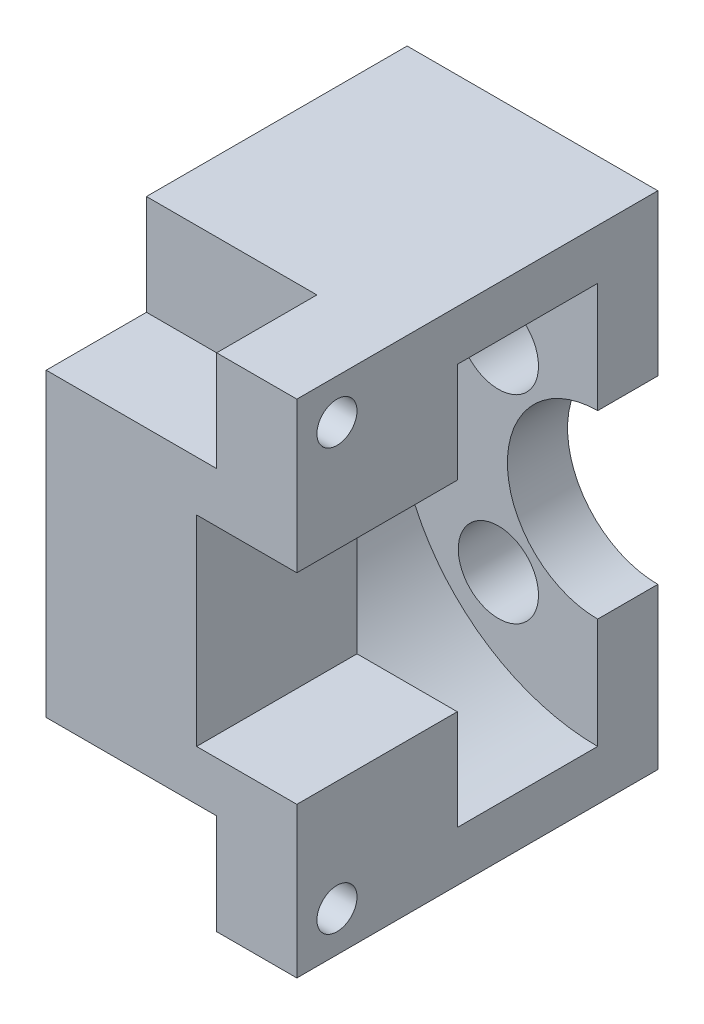
SolidWorks part; units mm, degrees
ref_plane "前视基准面" through (0, 0, 0) normal (0, 0, 1) x (1, 0, 0)
ref_plane "上视基准面" through (0, 0, 0) normal (0, 1, 0) x (1, 0, 0)
ref_plane "右视基准面" through (0, 0, 0) normal (1, 0, 0) x (0, 0, -1)
sketch "草图1" plane through (0, 0, 0) normal (0, 0, 1) x (1, 0, 0)
  line L1 (-12.5, -12.5) -> (12.5, -12.5)
  line L2 (-12.5, -12.5) -> (-12.5, 12.5)
  line L3 (-12.5, 12.5) -> (12.5, 12.5)
  line L4 (12.5, -12.5) -> (12.5, 12.5)
  line L5 (-12.5, -12.5) -> (12.5, 12.5) construction
  line L6 (-12.5, 12.5) -> (12.5, -12.5) construction
  point P0 (0, 0)
  dimension "D1" = 25
  dimension "D2" = 25
extrude "凸台-拉伸1" add sketch "草图1" along normal blind 10
sketch "草图2" plane through (0, 0, 10) normal (0, 0, 1) x (1, 0, 0)
  circle A0 centre (0, 0) radius 10
  dimension "D1" = 20
extrude "切除-拉伸1" cut sketch "草图2" against normal offset from surface (7 mm away) 3 up to face at (0, 0, 0)
sketch "草图3" plane through (0, 0, 3) normal (0, 0, 1) x (1, 0, 0)
  circle A0 centre (0, 0) radius 4.5
  dimension "D1" = 9
extrude "切除-拉伸2" cut sketch "草图3" against normal through all
sketch "草图4" plane through (0, 0, 3) normal (0, 0, 1) x (1, 0, 0)
  line L0 (-12.5, 12.5) -> (0, 0) construction
  circle A0 centre (-4.9497, 4.9497) radius 2
  dimension "D1" = 4
  dimension "D2" = 7
extrude "切除-拉伸4" cut sketch "草图4" against normal through all
pattern_circular "阵列(圆周)1" count 4 over 360 about axis through (0, 0, 0) along (0, 0, 1) of "切除-拉伸4"
sketch "草图5" plane through (0, 0, 10) normal (0, 0, 1) x (1, 0, 0)
  line L0 (-12.5, -12.5) -> (12.5, -12.5) construction
  line L1 (12.5, -12.5) -> (12.5, 12.5) construction
  line L2 (12.5, 12.5) -> (-12.5, 12.5) construction
  line L3 (-12.5, 12.5) -> (-12.5, -12.5) construction
  line L4 (-12.5, -12.5) -> (12.5, -12.5)
  line L5 (12.5, -12.5) -> (12.5, 12.5)
  line L6 (12.5, 12.5) -> (-12.5, 12.5)
  line L7 (-12.5, 12.5) -> (-12.5, -12.5)
extrude "凸台-拉伸2" add sketch "草图5" along normal blind 8
sketch "草图6" plane through (0, 0, 18) normal (0, 0, 1) x (1, 0, 0)
  line L1 (-5, -5) -> (5, -5)
  line L2 (-5, -5) -> (-5, 5)
  line L3 (-5, 5) -> (5, 5)
  line L4 (5, -5) -> (5, 5)
  line L5 (-5, -5) -> (5, 5) construction
  line L6 (-5, 5) -> (5, -5) construction
  point P0 (0, 0)
  dimension "D1" = 10
  dimension "D2" = 10
extrude "切除-拉伸5" cut sketch "草图6" against normal blind 8
sketch "草图7" plane through (0, 0, 18) normal (0, 0, 1) x (1, 0, 0)
  line L0 (-12.5, -12.5) -> (12.5, -12.5) construction
  line L1 (12.5, -12.5) -> (12.5, 12.5) construction
  line L2 (12.5, 12.5) -> (-12.5, 12.5) construction
  line L3 (-12.5, 12.5) -> (-12.5, -12.5) construction
  line L4 (-12.5, -12.5) -> (12.5, -12.5)
  line L5 (12.5, -12.5) -> (12.5, 12.5)
  line L6 (12.5, 12.5) -> (-12.5, 12.5)
  line L7 (-12.5, 12.5) -> (-12.5, -12.5)
  line L8 (5, 5) -> (-5, 5) construction
  line L9 (-9, -9) -> (9, -9)
  line L10 (-9, -9) -> (-9, 9)
  line L11 (-9, 9) -> (9, 9)
  line L12 (9, -9) -> (9, 9)
  line L13 (-9, -9) -> (9, 9) construction
  line L14 (-9, 9) -> (9, -9) construction
  line L15 (5, -5) -> (5, 5) construction
  line L17 (-12.5, -12.5) -> (12.5, -12.5)
  line L18 (-12.5, -12.5) -> (-12.5, 12.5)
  line L19 (-12.5, 12.5) -> (12.5, 12.5)
  line L20 (12.5, -12.5) -> (12.5, 12.5)
  line L21 (-12.5, -12.5) -> (12.5, 12.5) construction
  line L22 (-12.5, 12.5) -> (12.5, -12.5) construction
  point P2 (0, 0)
  point P14 (0, 0)
  dimension "D1" = 4
  dimension "D2" = 4
sketch "草图8" plane through (0, -12.5, 0) normal (0, -1, 0) x (1, 0, 0)
  line L1 (0, 0) -> (17.4478, 0)
  line L2 (0, 0) -> (0, 20.9451)
  line L3 (0, 20.9451) -> (17.4478, 20.9451)
  line L4 (17.4478, 0) -> (17.4478, 20.9451)
extrude "切除-拉伸8" cut sketch "草图8" against normal through all
sketch "草图12" plane through (0, 0, 0) normal (1, 0, 0) x (0, 0, -1)
  line L1 (-18, -12.5) -> (-13, -12.5)
  line L2 (-18, -12.5) -> (-18, -7.5)
  line L3 (-18, -7.5) -> (-13, -7.5)
  line L4 (-13, -12.5) -> (-13, -7.5)
  dimension "D1" = 5
  dimension "D2" = 5
extrude "切除-拉伸9" cut sketch "草图12" against normal through all from offset 4 offset against normal yes
mirror "镜向1" about plane through (0, 0, 0) normal (0, 1, 0) of "切除-拉伸9"
sketch "草图13" plane through (-4, 0, 0) normal (-1, 0, 0) x (0, 0, 1)
  line L0 (18, -12.5) -> (13, -12.5) construction
  line L1 (18, -12.5) -> (18, 12.5) construction
  circle A0 centre (16, -10.5) radius 1
  dimension "D1" = 2
  dimension "D2" = 2
  dimension "D3" = 2
extrude "切除-拉伸10" cut sketch "草图13" against normal through all
mirror "镜向2" about plane through (0, 0, 0) normal (0, 1, 0) of "切除-拉伸10"
